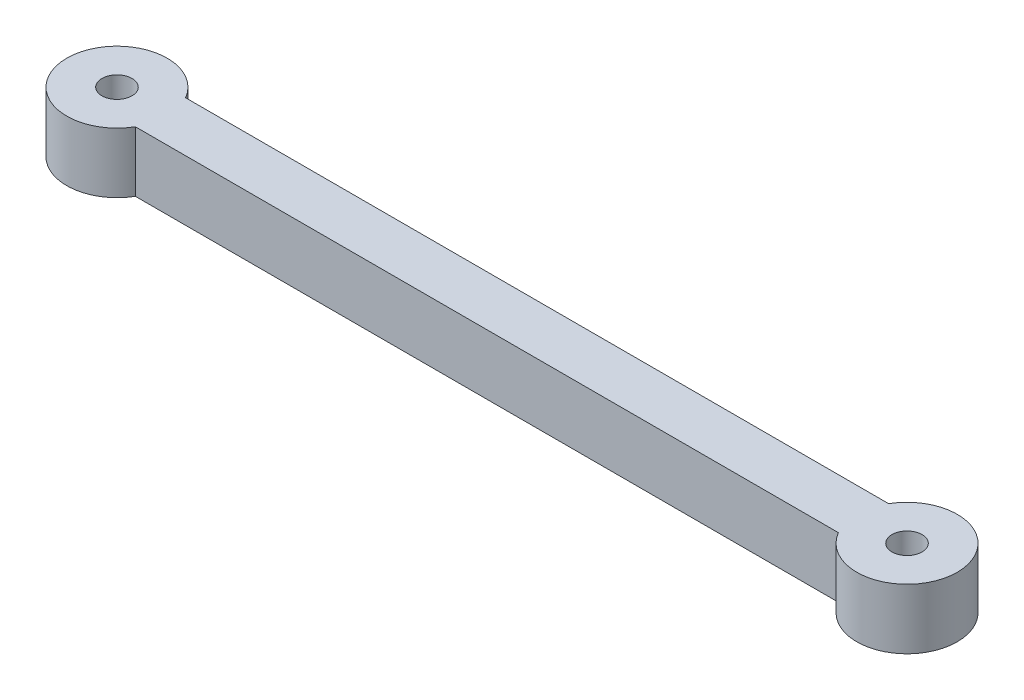
SolidWorks part; units mm, degrees
ref_plane "Front Plane" through (0, 0, 0) normal (0, 0, 1) x (1, 0, 0)
ref_plane "Top Plane" through (0, 0, 0) normal (0, 1, 0) x (1, 0, 0)
ref_plane "Right Plane" through (0, 0, 0) normal (1, 0, 0) x (0, 0, -1)
sketch "Sketch1" plane through (0, 0, 0) normal (0, 1, 0) x (1, 0, 0)
  line L0 (-35, 2.5) -> (35, 2.5)
  line L1 (-35, -2.5) -> (35, -2.5)
  line L2 (-55, 0) -> (55, 0) construction
  arc A1 (-35, 2.5) -> (-35, -2.5) centre (-39.3301, 0) ccw
  arc A2 (35, 2.5) -> (35, -2.5) centre (39.3301, 0) cw
  dimension "D2" = 35
  dimension "D3" = 5
  dimension "D7" = 5
  dimension "D1" = 5
  dimension "D4" = 70
  dimension "D5" = 70
  dimension "D6" = 2.5
extrude "Boss-Extrude1" add sketch "Sketch1" along normal blind 6
sketch "Sketch2" plane through (0, 6, 0) normal (0, 1, 0) x (1, 0, 0)
  circle A0 centre (-39.3301, 0) radius 1.5
  circle A1 centre (39.3301, 0) radius 1.5
  dimension "D1" = 3
  dimension "D2" = 3
extrude "Cut-Extrude1" cut sketch "Sketch2" against normal through all
